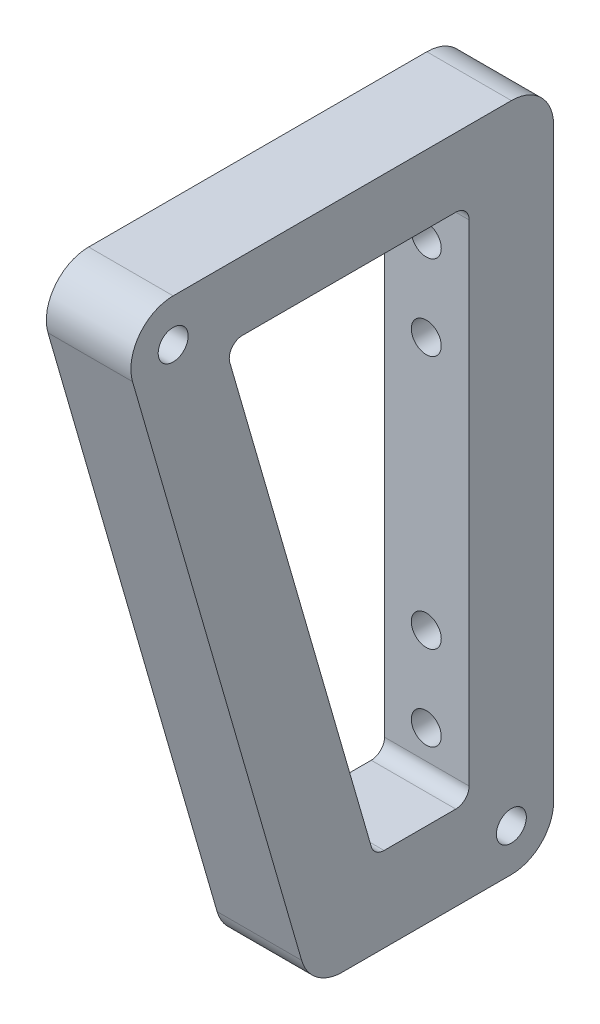
SolidWorks part; units mm, degrees
ref_plane "Front Plane" through (0, 0, 0) normal (0, 0, 1) x (1, 0, 0)
ref_plane "Top Plane" through (0, 0, 0) normal (0, 1, 0) x (1, 0, 0)
ref_plane "Right Plane" through (0, 0, 0) normal (1, 0, 0) x (0, 0, -1)
sketch "Sketch1" plane through (0, 0, 0) normal (1, 0, 0) x (0, 0, -1)
  line L0 (-50.8, 87.9882) -> (0, 0) construction
  line L1 (0, 0) -> (0, 87.9882) construction
  line L2 (0, 87.9882) -> (-50.8, 87.9882) construction
  line L4 (6.35, -6.35) -> (6.35, 94.3382)
  line L5 (6.35, 94.3382) -> (-59.2424, 94.3382)
  line L7 (-6.35, 6.35) -> (-6.35, 83.9882)
  line L8 (-6.35, 83.9882) -> (-43.036, 83.9882)
  line L9 (0, 0) -> (-25.4, 0) construction
  line L10 (-25.4, 0) -> (-50.8, 87.9882) construction
  line L11 (-43.036, 83.9882) -> (-20.6238, 6.35)
  line L12 (-20.6238, 6.35) -> (-6.35, 6.35)
  line L13 (-59.2424, 94.3382) -> (-30.1762, -6.35)
  line L14 (-30.1762, -6.35) -> (6.35, -6.35)
  circle A0 centre (0, 0) radius 2.25
  circle A1 centre (-50.8, 87.9882) radius 2.25
  dimension "D3" = 4.5
  dimension "D4" = 4.5
  dimension "D1" = 30
  dimension "D2" = 101.6
  dimension "D5" = 6.35
  dimension "D6" = 12.7
  dimension "D7" = 25.4
  dimension "D8" = 12.7
  dimension "D9" = 12.7
  dimension "D10" = 4
extrude "Boss-Extrude1" add sketch "Sketch1" along normal blind 12.7
sketch "Sketch3" plane through (0, 0, -6.35) normal (0, 0, -1) x (-1, 0, 0)
  line L0 (0, -6.35) -> (0, 94.3382) construction
  circle A0 centre (-6.2699, 76.2) radius 2.25
  circle A1 centre (-6.2699, 63.5) radius 2.25
  circle A2 centre (-6.2699, 12.7) radius 2.25
  circle A3 centre (-6.2699, 25.4) radius 2.25
  point P10 (0, 0)
  dimension "D5" = 4.5
  dimension "D1" = 12.7
  dimension "D2" = 12.7
  dimension "D3" = 6.2699
  dimension "D4" = 12.7
  dimension "D6" = 38.1
extrude "Cut-Extrude1" cut sketch "Sketch3" against normal up to next
fillet "Fillet3" radius 6.35 4 edges at (6.35, 94.3382, -6.35) (6.35, 94.3382, 59.2424) (6.35, -6.35, 30.1762) (6.35, -6.35, -6.35)
fillet "Fillet4" radius 2 4 edges at (6.35, 6.35, 20.6238) (6.35, 6.35, 6.35) (6.35, 83.9882, 6.35) (6.35, 83.9882, 43.036)
